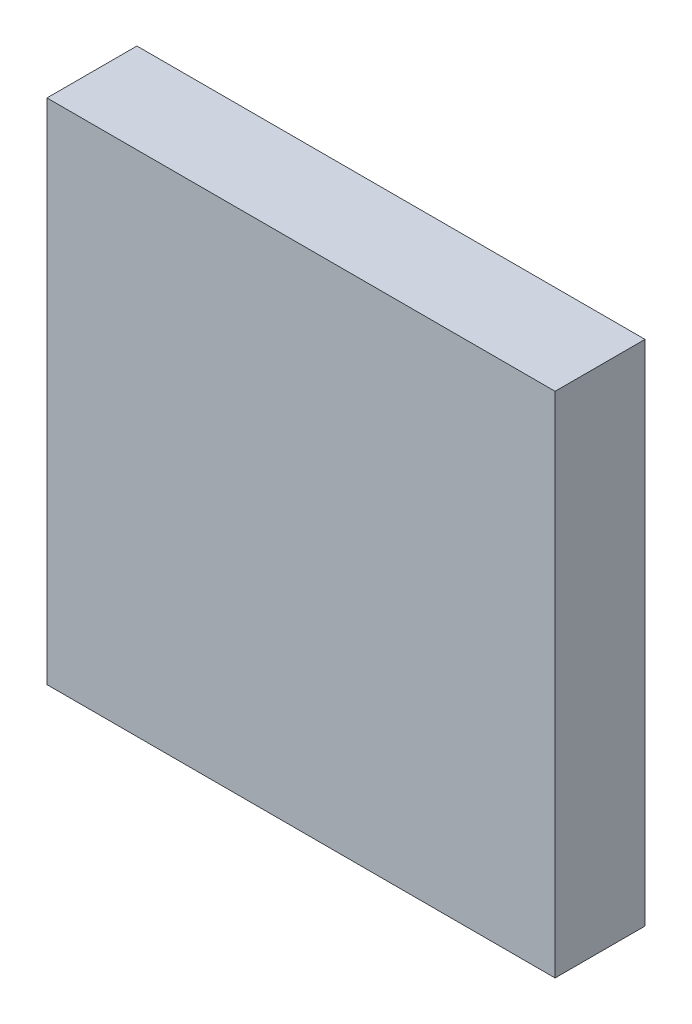
SolidWorks part; units mm, degrees
ref_plane "Front Plane" through (0, 0, 0) normal (0, 0, 1) x (1, 0, 0)
ref_plane "Top Plane" through (0, 0, 0) normal (0, 1, 0) x (1, 0, 0)
ref_plane "Right Plane" through (0, 0, 0) normal (1, 0, 0) x (0, 0, -1)
sketch "Sketch1" plane through (0, 0, 0) normal (0, 0, 1) x (1, 0, 0)
  line L1 (-56.5, -56.5) -> (56.5, -56.5)
  line L2 (-56.5, -56.5) -> (-56.5, 56.5)
  line L3 (-56.5, 56.5) -> (56.5, 56.5)
  line L4 (56.5, -56.5) -> (56.5, 56.5)
  line L5 (-56.5, -56.5) -> (56.5, 56.5) construction
  line L6 (-56.5, 56.5) -> (56.5, -56.5) construction
  point P0 (0, 0)
  dimension "D1" = 113
  dimension "D2" = 113
extrude "Boss-Extrude1" add sketch "Sketch1" along normal blind 20
